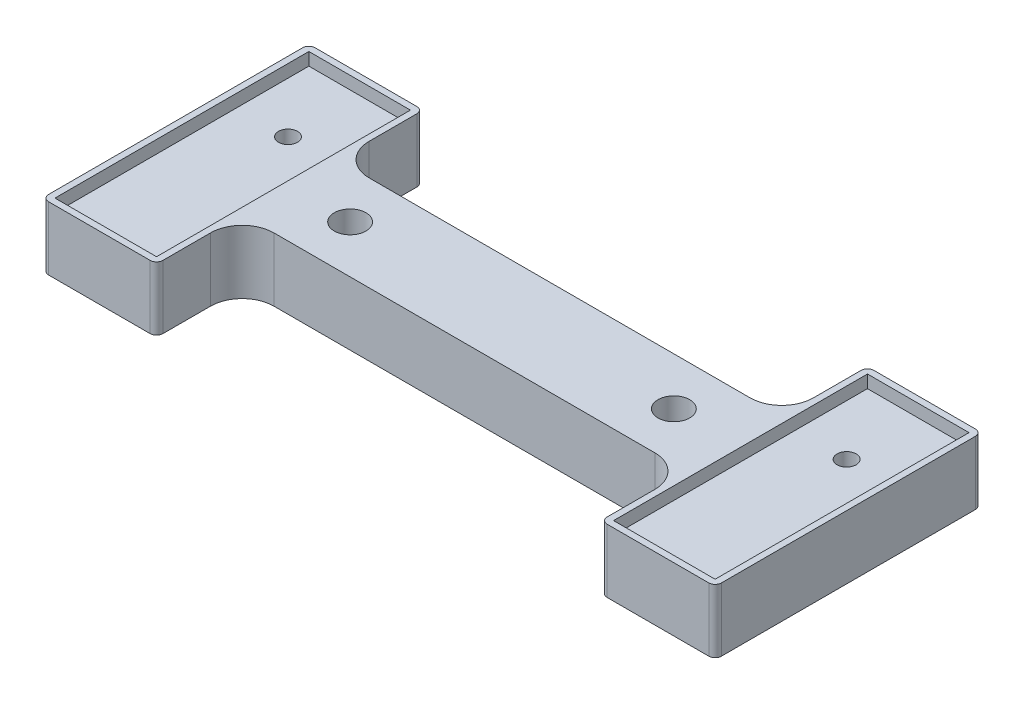
SolidWorks part; units mm, degrees
ref_plane "Front Plane" through (0, 0, 0) normal (0, 0, 1) x (1, 0, 0)
ref_plane "Top Plane" through (0, 0, 0) normal (0, 1, 0) x (1, 0, 0)
ref_plane "Right Plane" through (0, 0, 0) normal (1, 0, 0) x (0, 0, -1)
sketch "Sketch1" plane through (0, 0, 0) normal (0, 1, 0) x (1, 0, 0)
  line L0 (0, -39.6) -> (0, 39.6) construction
  line L1 (-35, 7.5) -> (35, 7.5)
  line L2 (-35, 7.5) -> (-35, -7.5)
  line L3 (-35, -7.5) -> (35, -7.5)
  line L4 (35, 7.5) -> (35, -7.5)
  line L5 (-35, 7.5) -> (35, -7.5) construction
  line L6 (-35, -7.5) -> (35, 7.5) construction
  line L7 (-25.5, 0) -> (25.5, 0) construction
  line L13 (35, 21) -> (53, 21)
  line L14 (-53, 21) -> (-35, 21)
  line L18 (-53, 21) -> (-53, -21)
  line L19 (-53, -21) -> (-35, -21)
  line L20 (-35, 21) -> (-35, -21)
  line L21 (-53, 21) -> (-35, -21) construction
  line L22 (-53, -21) -> (-35, 21) construction
  line L23 (35, 21) -> (35, -21)
  line L24 (35, -21) -> (53, -21)
  line L25 (53, 21) -> (53, -21)
  circle A2 centre (-25.5, 0) radius 2.5
  circle A3 centre (25.5, 0) radius 2.5
  point P0 (0, 0)
  point P5 (-44, 0)
  point P21 (0, 0)
  point P22 (0, 0)
  dimension "D4" = 5
  dimension "D1" = 70
  dimension "D2" = 15
  dimension "D3" = 51
  dimension "D5" = 42
  dimension "D6" = 18
extrude "Boss-Extrude2" add sketch "Sketch1" along normal blind 10 contours L20 L14 L18 L19 L2 | L4 L1 L2 L3 A3 A2 | L25 L13 L23 L4 L24
fillet "Fillet1" radius 5 4 edges at (-35, 5, -7.5) (35, 5, 7.5) (35, 5, -7.5) (-35, 5, 7.5)
sketch "Sketch4" plane through (0, 10, 0) normal (0, 1, 0) x (1, 0, 0)
  line L0 (-53, 21) -> (-35, -21) construction
  line L1 (-52, 20) -> (-36, 20)
  line L2 (-52, 20) -> (-52, -20)
  line L3 (-52, -20) -> (-36, -20)
  line L4 (-36, 20) -> (-36, -20)
  line L5 (-52, 20) -> (-36, -20) construction
  line L6 (-52, -20) -> (-36, 20) construction
  point P0 (-44, 0)
  point P7 (0, 0)
  point P9 (0, 0)
  point P11 (0, 0)
  point P12 (-44, 0)
  dimension "D1" = 16
  dimension "D2" = 40
extrude "Cut-Extrude2" cut sketch "Sketch4" against normal blind 2
mirror "Mirror3" about plane through (0, 0, 0) normal (1, 0, 0) of "Cut-Extrude2"
sketch "Sketch5" plane through (0, 8, 0) normal (0, 1, 0) x (1, 0, 0)
  line L0 (44, 8.71) -> (44, 20) construction
  line L1 (36, 20) -> (52, 20) construction
  circle A0 centre (44, 8.71) radius 1.5
  point P2 (0, 0)
  dimension "D2" = 3
  dimension "D1" = 11.29
extrude "Cut-Extrude3" cut sketch "Sketch5" against normal through all both and the other way through all
mirror "Mirror4" about plane through (0, 0, 0) normal (1, 0, 0) of "Cut-Extrude3"
fillet "Fillet2" radius 1 8 edges at (53, 5, -21) (-35, 5, -21) (35, 5, -21) (-53, 5, -21) (-35, 5, 21) (-53, 5, 21) (53, 5, 21) (35, 5, 21)
